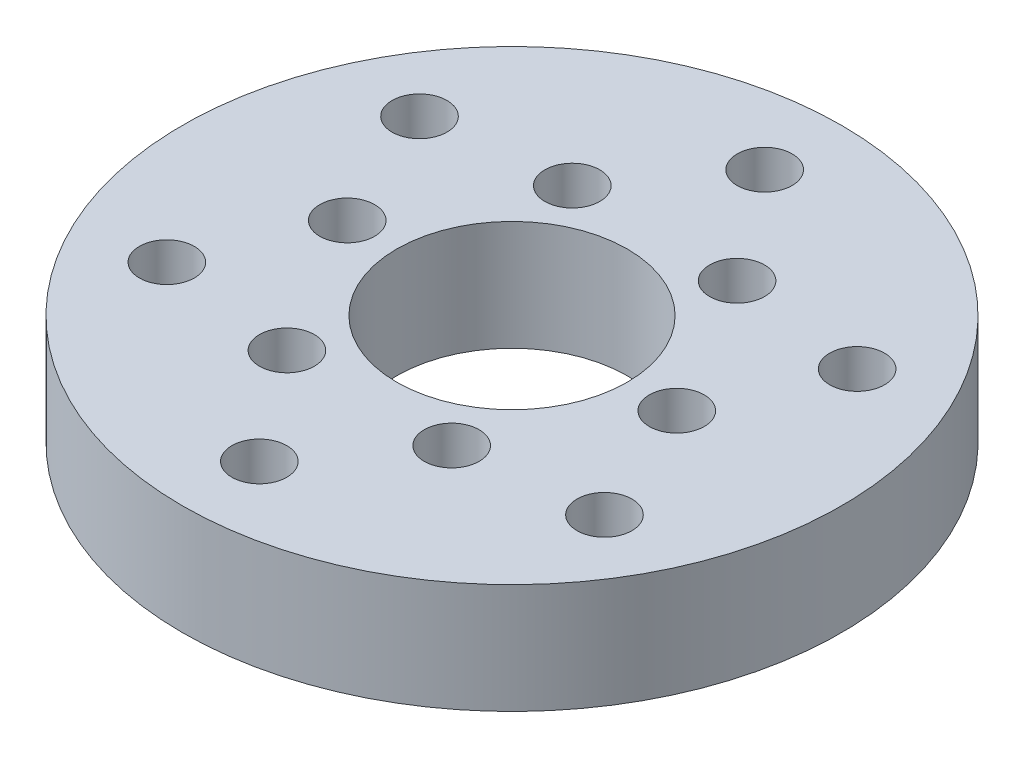
SolidWorks part; units mm, degrees
ref_plane "Front Plane" through (0, 0, 0) normal (0, 0, 1) x (1, 0, 0)
ref_plane "Top Plane" through (0, 0, 0) normal (0, 1, 0) x (1, 0, 0)
ref_plane "Right Plane" through (0, 0, 0) normal (1, 0, 0) x (0, 0, -1)
sketch "Sketch1" plane through (0, 0, 0) normal (0, 1, 0) x (1, 0, 0)
  circle A0 centre (0, 0) radius 30
  circle A1 centre (0, 0) radius 23 construction
  circle A2 centre (0, 23) radius 2.5
  circle A3 centre (19.9186, 11.5) radius 2.5
  circle A4 centre (19.9186, -11.5) radius 2.5
  circle A5 centre (0, -23) radius 2.5
  circle A6 centre (-19.9186, -11.5) radius 2.5
  circle A7 centre (-19.9186, 11.5) radius 2.5
  circle A8 centre (0, 0) radius 10.5
  point P18 (0, 0)
  dimension "D1" = 46
  dimension "D2" = 5
  dimension "D4" = 60
  dimension "D5" = 21
  dimension "D3" = 6
extrude "Boss-Extrude1" add sketch "Sketch1" along normal blind 10
sketch "Sketch2" plane through (0, 10, 0) normal (0, 1, 0) x (1, 0, 0)
  line L0 (-7.5, 12.9904) -> (0, 0) construction
  line L1 (0, 0) -> (7.6183, 0) construction
  circle A0 centre (0, 0) radius 15 construction
  circle A1 centre (-7.5, 12.9904) radius 2.5
  circle A2 centre (7.5, 12.9904) radius 2.5
  circle A3 centre (15, 0) radius 2.5
  circle A4 centre (7.5, -12.9904) radius 2.5
  circle A5 centre (-7.5, -12.9904) radius 2.5
  circle A6 centre (-15, 0) radius 2.5
  point P18 (0, 0)
  dimension "D1" = 30
  dimension "D3" = 5
  dimension "D2" = 120
  dimension "D4" = 6
extrude "Cut-Extrude1" cut sketch "Sketch2" against normal blind 10
